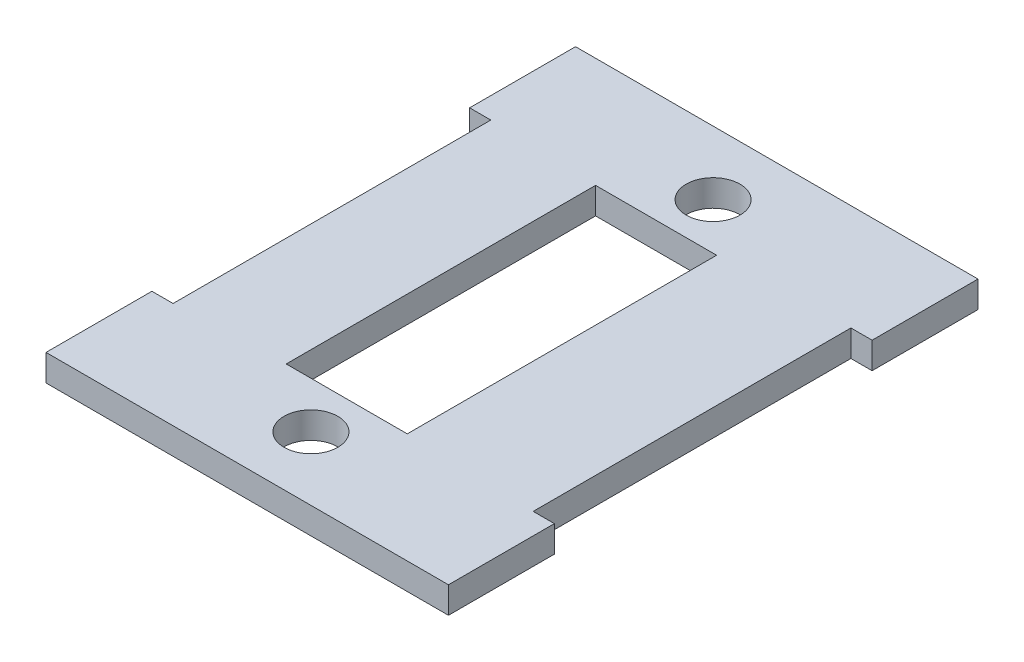
SolidWorks part; units mm, degrees
ref_plane "Piano frontale" through (0, 0, 0) normal (0, 0, 1) x (1, 0, 0)
ref_plane "Piano superiore" through (0, 0, 0) normal (0, 1, 0) x (1, 0, 0)
ref_plane "Piano destro" through (0, 0, 0) normal (1, 0, 0) x (0, 0, -1)
sketch "Schizzo2" plane through (0, 0, 0) normal (0, 1, 0) x (1, 0, 0)
  line L0 (-16, 45) -> (-16, -115) construction
  line L1 (-18, 15) -> (-16, 15)
  line L3 (5.715, -14.605) -> (-5.715, -14.605)
  line L18 (20, 15) -> (18, 15)
  line L19 (-18, 25) -> (-18, 15)
  line L20 (-18, -25) -> (-18, -15)
  line L22 (18, -15) -> (18, 15)
  line L25 (5.715, 14.605) -> (-5.715, -14.605) construction
  line L26 (20, 25) -> (-18, 25)
  line L27 (5.715, 14.605) -> (-5.715, 14.605)
  line L28 (-18, -25) -> (20, -25)
  line L29 (-5.715, -14.605) -> (-5.715, 14.605)
  line L30 (5.715, -14.605) -> (-5.715, 14.605) construction
  line L31 (20, -15) -> (18, -15)
  line L32 (20, 25) -> (20, 15)
  line L33 (20, -25) -> (20, -15)
  line L34 (-18, -15) -> (-16, -15)
  line L35 (5.715, -14.605) -> (5.715, 14.605)
  line L36 (-16, -15) -> (-16, 15)
  line L37 (1, -25) -> (1, 25) construction
  line L38 (-16, 0) -> (18, 0) construction
  circle A2 centre (1, 18.9854) radius 2.54
  circle A3 centre (1, -18.9854) radius 2.54
  dimension "D5" = 50
  dimension "D8" = 38
  dimension "D9" = 37.9707
  dimension "D10" = 10
  dimension "D11" = 34
extrude "Estrusione-Estrusione1" add sketch "Schizzo2" along normal mid plane 2.5
